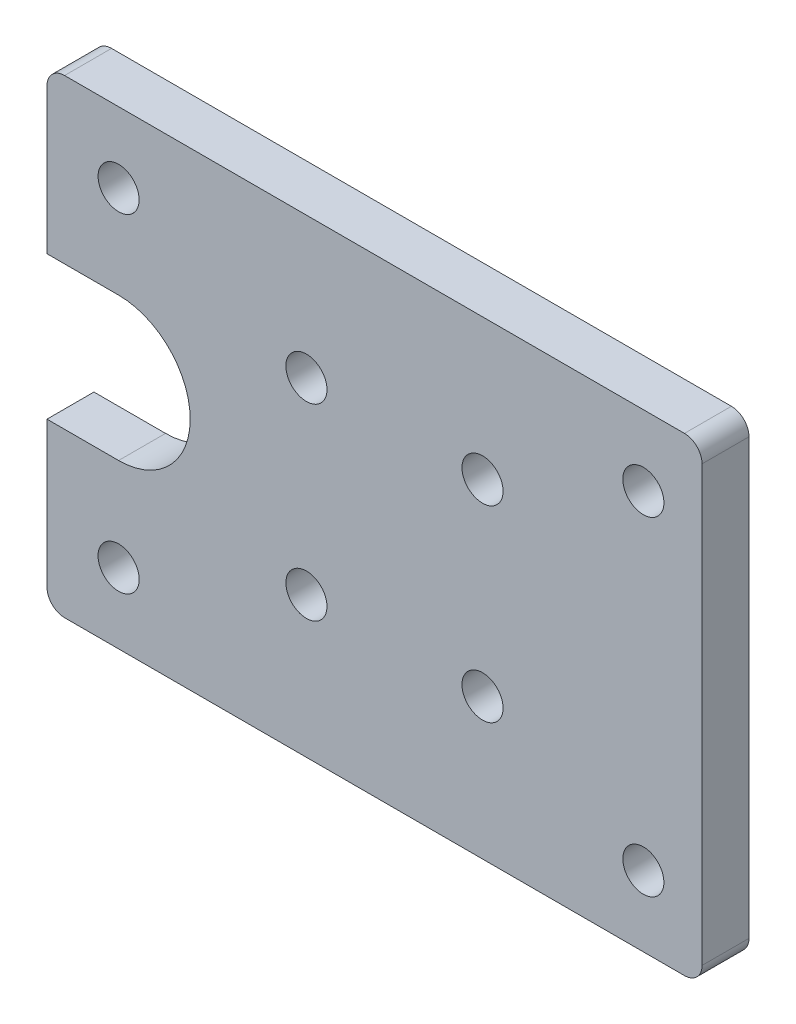
SolidWorks part; units mm, degrees
ref_plane "Спереди" through (0, 0, 0) normal (0, 0, 1) x (1, 0, 0)
ref_plane "Сверху" through (0, 0, 0) normal (0, 1, 0) x (1, 0, 0)
ref_plane "Справа" through (0, 0, 0) normal (1, 0, 0) x (0, 0, -1)
sketch "Эскиз1" plane through (0, 0, 0) normal (0, 0, 1) x (1, 0, 0)
  line L1 (31.5, -20) -> (-31.5, -20)
  line L2 (33, -18.5) -> (33, 18.5)
  line L3 (31.5, 20) -> (-31.5, 20)
  line L4 (-33, -18.5) -> (-33, 18.5)
  line L5 (33, -20) -> (-33, 20) construction
  line L6 (33, 20) -> (-33, -20) construction
  arc A0 (-31.5, -20) -> (-33, -18.5) centre (-31.5, -18.5) cw
  arc A1 (-33, 18.5) -> (-31.5, 20) centre (-31.5, 18.5) cw
  arc A2 (31.5, -20) -> (33, -18.5) centre (31.5, -18.5) ccw
  arc A3 (33, 18.5) -> (31.5, 20) centre (31.5, 18.5) ccw
  point P0 (0, 0)
  dimension "D3" = 1.5
  dimension "D4" = 1.5
  dimension "D1" = 66
  dimension "D2" = 40
extrude "Бобышка-Вытянуть2" add sketch "Эскиз1" along normal blind 4
sketch "Эскиз4" plane through (0, 0, 0) normal (0, 0, -1) x (-1, 0, 0)
  line L0 (33, 0) -> (-33, 0) construction
  line L1 (33, 18.5) -> (33, -18.5) construction
  line L2 (-33, -18.5) -> (-33, 18.5) construction
  line L4 (8.2, 20) -> (8.2, -20) construction
  line L5 (-31.5, 20) -> (31.5, 20) construction
  line L6 (31.5, -20) -> (-31.5, -20) construction
  line L7 (13.7, 20) -> (13.7, -20) construction
  line L8 (-33, -18.5) -> (-33, 18.5) construction
  circle A0 centre (21.7, 0) radius 6.1
  circle A1 centre (21.7, -14) radius 1.75
  circle A2 centre (5.7, -8) radius 1.75
  circle A3 centre (-9.3, -8) radius 1.75
  circle A4 centre (-23, -14) radius 1.75
  circle A5 centre (21.7, 14) radius 1.75
  circle A6 centre (5.7, 8) radius 1.75
  circle A7 centre (-9.3, 8) radius 1.75
  circle A8 centre (-23, 14) radius 1.75
  dimension "D2" = 5.7
  dimension "D6" = 15
  dimension "D7" = 6
  dimension "D9" = 12.2
  dimension "D10" = 3.5
  dimension "D11" = 3.5
  dimension "D12" = 3.5
  dimension "D13" = 3.5
  dimension "D3" = 16
  dimension "D4" = 14
  dimension "D5" = 8
  dimension "D8" = 10
  dimension "D14" = 2.5
  dimension "D15" = 8
extrude "Вырез-Вытянуть1" cut sketch "Эскиз4" against normal through all
sketch "Эскиз5" plane through (0, 0, 0) normal (0, 0, -1) x (-1, 0, 0)
  line L0 (-31.5, 20) -> (31.5, 20) construction
  line L1 (27.8, 20) -> (33, 20)
  line L2 (27.8, 20) -> (27.8, 6.1)
  line L3 (27.8, -20) -> (33, -20)
  line L4 (33, 20) -> (33, -20)
  line L5 (33, 18.5) -> (33, -18.5) construction
  line L6 (21.7, 6.1) -> (21.7, -6.1) construction
  line L7 (21.7, 6.1) -> (27.8, 6.1)
  line L8 (21.7, 6.1) -> (21.7, -6.1)
  line L9 (21.7, -6.1) -> (27.8, -6.1)
  line L10 (-31.5, 20) -> (31.5, 20) construction
  line L11 (27.8, -6.1) -> (27.8, -20)
  line L12 (-28, 20) -> (-33, 20)
  line L13 (-28, 20) -> (-28, -20)
  line L14 (-28, -20) -> (-33, -20)
  line L15 (-33, 20) -> (-33, -20)
  line L18 (31.5, -20) -> (-31.5, -20) construction
  line L19 (-33, -18.5) -> (-33, 18.5) construction
  circle A0 centre (21.7, 0) radius 6.1 construction
  point P10 (33, 0)
  dimension "D1" = 5
extrude "Вырез-Вытянуть2" cut sketch "Эскиз5" against normal up to surface (4 mm away) up to face at (-23.45, -14, 4)
fillet "Скругление1" radius 1.5 4 edges at (28, 20, 2) (28, -20, 2) (-27.8, -20, 2) (-27.8, 20, 2)
sketch "Эскиз7" plane through (0, 0, 0) normal (0, 0, -1) x (-1, 0, 0)
  line L0 (8.2, 20) -> (8.2, -20) construction
  line L1 (-26.5, 20) -> (26.3, 20) construction
  line L2 (26.3, -20) -> (-26.5, -20) construction
  line L3 (-9.3, -8) -> (5.7, 8) construction
  line L4 (-9.3, 8) -> (5.7, -8) construction
  line L5 (-1.8, 20) -> (-1.8, -20) construction
  line L6 (-11.8, 20) -> (-11.8, -20) construction
  point P16 (-1.8, 0)
  dimension "D1" = 10
